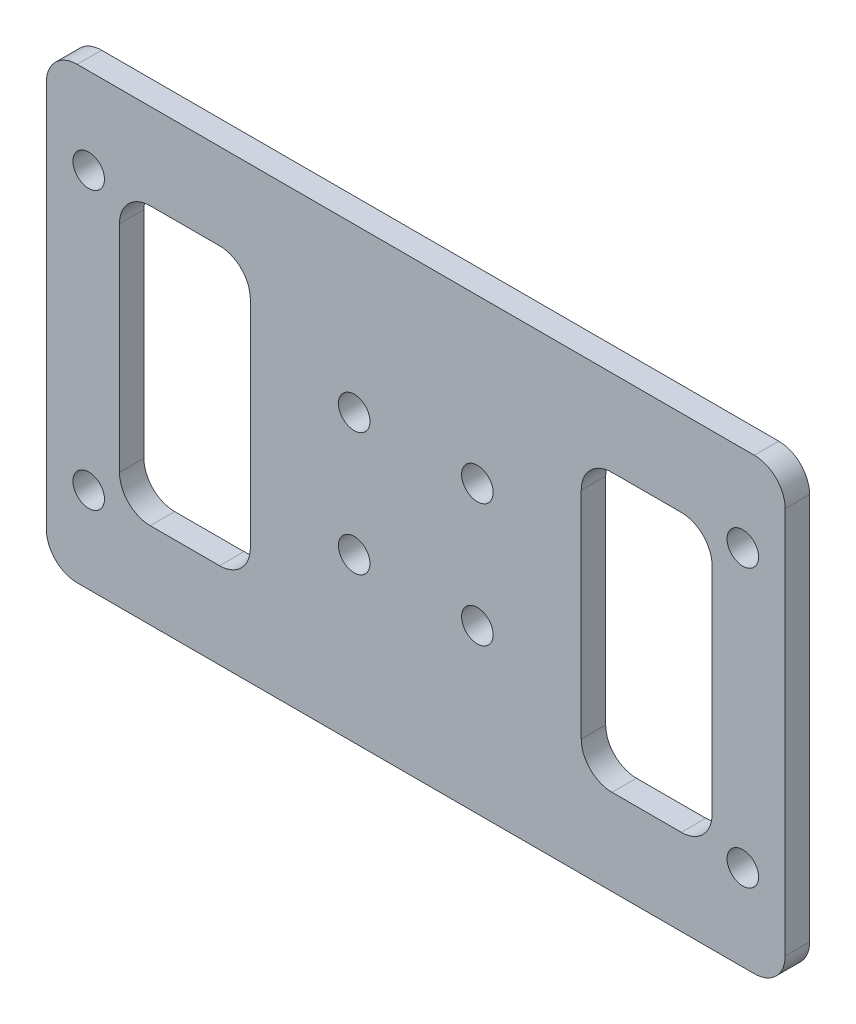
SolidWorks part; units mm, degrees
ref_plane "Front Plane" through (0, 0, 0) normal (0, 0, 1) x (1, 0, 0)
ref_plane "Top Plane" through (0, 0, 0) normal (0, 1, 0) x (1, 0, 0)
ref_plane "Right Plane" through (0, 0, 0) normal (1, 0, 0) x (0, 0, -1)
sketch "Sketch1" plane through (0, 0, 0) normal (0, 0, 1) x (1, 0, 0)
  line L0 (-38.5, 18) -> (-38.5, -18)
  line L1 (42.5, -18) -> (-42.5, -18) construction
  line L2 (42.5, -18) -> (42.5, 18) construction
  line L3 (42.5, 18) -> (-42.5, 18) construction
  line L4 (-42.5, -18) -> (-42.5, 18) construction
  line L5 (42.5, -18) -> (-42.5, 18) construction
  line L6 (42.5, 18) -> (-42.5, -18) construction
  line L7 (48, -29.175) -> (-48, -29.175)
  line L8 (48, -29.175) -> (48, 29.175)
  line L9 (48, 29.175) -> (-48, 29.175)
  line L10 (-48, -29.175) -> (-48, 29.175)
  line L11 (48, -29.175) -> (-48, 29.175) construction
  line L12 (48, 29.175) -> (-48, -29.175) construction
  line L13 (21.5, -21.5) -> (-21.5, -21.5) construction
  line L14 (21.5, -21.5) -> (21.5, 21.5) construction
  line L15 (21.5, 21.5) -> (-21.5, 21.5) construction
  line L16 (-21.5, -21.5) -> (-21.5, 21.5) construction
  line L17 (21.5, -21.5) -> (-21.5, 21.5) construction
  line L18 (21.5, 21.5) -> (-21.5, -21.5) construction
  line L19 (-8, -8) -> (8, -8) construction
  line L20 (-8, -8) -> (-8, 8) construction
  line L21 (-8, 8) -> (8, 8) construction
  line L22 (8, -8) -> (8, 8) construction
  line L23 (-8, -8) -> (8, 8) construction
  line L24 (-8, 8) -> (8, -8) construction
  line L25 (-38.5, -18) -> (-21.5, -18)
  line L26 (-21.5, -18) -> (-21.5, 18)
  line L27 (-21.5, 18) -> (-38.5, 18)
  line L28 (0, 0) -> (0, 50000) construction
  line L29 (21.5, -18) -> (21.5, 18)
  line L30 (38.5, -18) -> (21.5, -18)
  line L31 (38.5, 18) -> (38.5, -18)
  line L32 (21.5, 18) -> (38.5, 18)
  circle A0 centre (-42.5, 18) radius 2.05
  circle A1 centre (-42.5, -18) radius 2.05
  circle A2 centre (42.5, 18) radius 2.05
  circle A3 centre (42.5, -18) radius 2.05
  circle A4 centre (8, -8) radius 2.05
  circle A5 centre (-8, -8) radius 2.05
  circle A6 centre (-8, 8) radius 2.05
  circle A7 centre (8, 8) radius 2.05
  circle A8 centre (-42.5, 18) radius 4 construction
  circle A9 centre (-42.5, -18) radius 4 construction
  circle A10 centre (42.5, -18) radius 4 construction
  circle A11 centre (42.5, 18) radius 4 construction
  point P0 (0, 0)
  point P6 (0, 0)
  point P11 (0, 0)
  point P16 (0, 0)
  dimension "D7" = 4.1
  dimension "D8" = 8
  dimension "D1" = 96
  dimension "D2" = 58.35
  dimension "D3" = 85
  dimension "D4" = 36
  dimension "D5" = 43
  dimension "D6" = 16
extrude "Boss-Extrude1" add sketch "Sketch1" along normal blind 3.175
fillet "Fillet1" radius 4 12 edges at (-48, -29.175, 1.5875) (-48, 29.175, 1.5875) (-38.5, -18, 1.5875) (-38.5, 18, 1.5875) (-21.5, 18, 1.5875) (-21.5, -18, 1.5875) (21.5, -18, 1.5875) (38.5, -18, 1.5875) (21.5, 18, 1.5875) (38.5, 18, 1.5875) (48, -29.175, 1.5875) (48, 29.175, 1.5875)
equation "\"w\"= 96mm'58."
equation "\"h\"= 58.35mm"
equation "\"iw\" = 85mm"
equation "\"ih\"= 36mm"
equation "\"outerSq\"= 43mm"
equation "\"innerSq\"= 16mm"
equation "\"sh\"= 4.1mm"
equation "\"D1@Sketch1\"=\"w\""
equation "\"D2@Sketch1\"=\"h\""
equation "\"D3@Sketch1\"=\"iw\""
equation "\"D4@Sketch1\"=\"ih\""
equation "\"D5@Sketch1\"=\"outerSq\""
equation "\"D6@Sketch1\"=\"innerSq\""
equation "\"D7@Sketch1\"=\"sh\""
equation "\"thick\" = 3.175mm"
equation "\"filet\"= 4mm"
equation "\"D1@Boss-Extrude1\"=\"thick\""
equation "\"D1@Fillet1\"=\"filet\""
